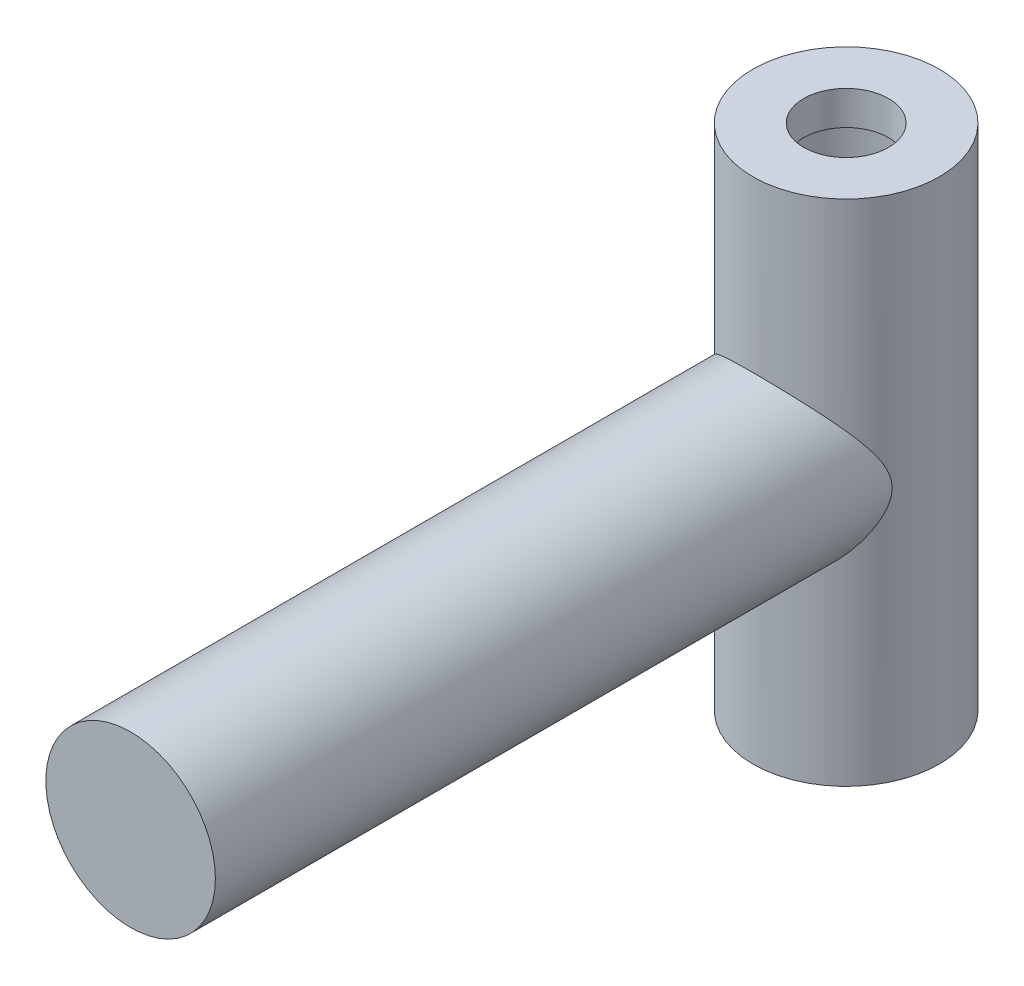
SolidWorks part; units mm, degrees
material "AISI 4340 Acero normalizado"
ref_plane "Alzado" through (0, 0, 0) normal (0, 0, 1) x (1, 0, 0)
ref_plane "Planta" through (0, 0, 0) normal (0, 1, 0) x (1, 0, 0)
ref_plane "Vista lateral" through (0, 0, 0) normal (1, 0, 0) x (0, 0, -1)
sketch "Croquis1" plane through (0, 0, 0) normal (0, 0, 1) x (1, 0, 0)
  circle A0 centre (0, 0) radius 5
extrude "Saliente-Extruir1" add sketch "Croquis1" against normal blind 40
sketch "Croquis2" plane through (0, 0, 0) normal (0, 1, 0) x (1, 0, 0)
  circle A0 centre (0, 42.2021) radius 5.5
  circle A1 centre (0, 42.2021) radius 3.75
extrude "Saliente-Extruir2" add sketch "Croquis2" along normal mid plane 30
sketch "Croquis3" plane through (0, 15, 0) normal (0, 1, 0) x (1, 0, 0)
  circle A0 centre (0, 42.2021) radius 3.75
extrude "Cortar-Extruir1" cut sketch "Croquis3" against normal blind 30
sketch "Croquis4" plane through (0, 15, 0) normal (0, 1, 0) x (1, 0, 0)
  circle A0 centre (0, 42.2021) radius 2.5
  circle A1 centre (0, 42.2021) radius 5.5
extrude "Saliente-Extruir3" add sketch "Croquis4" against normal blind 2
mirror "Simetría1" about plane through (0, 0, 0) normal (0, 1, 0) of "Saliente-Extruir3"
